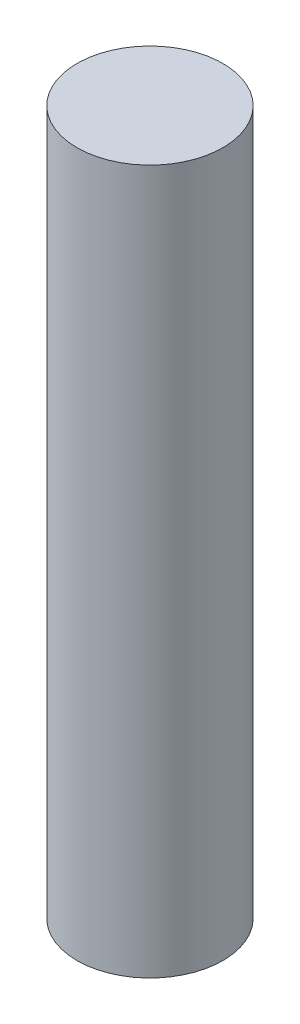
SolidWorks part; units mm, degrees
ref_plane "Front Plane" through (0, 0, 0) normal (0, 0, 1) x (1, 0, 0)
ref_plane "Top Plane" through (0, 0, 0) normal (0, 1, 0) x (1, 0, 0)
ref_plane "Right Plane" through (0, 0, 0) normal (1, 0, 0) x (0, 0, -1)
sketch "Sketch1" plane through (0, 0, 0) normal (0, 1, 0) x (1, 0, 0)
  circle A0 centre (0, 0) radius 29.8403
  dimension "D1" = 59.6806
extrude "Boss-Extrude1" add sketch "Sketch1" against normal blind 287.895
